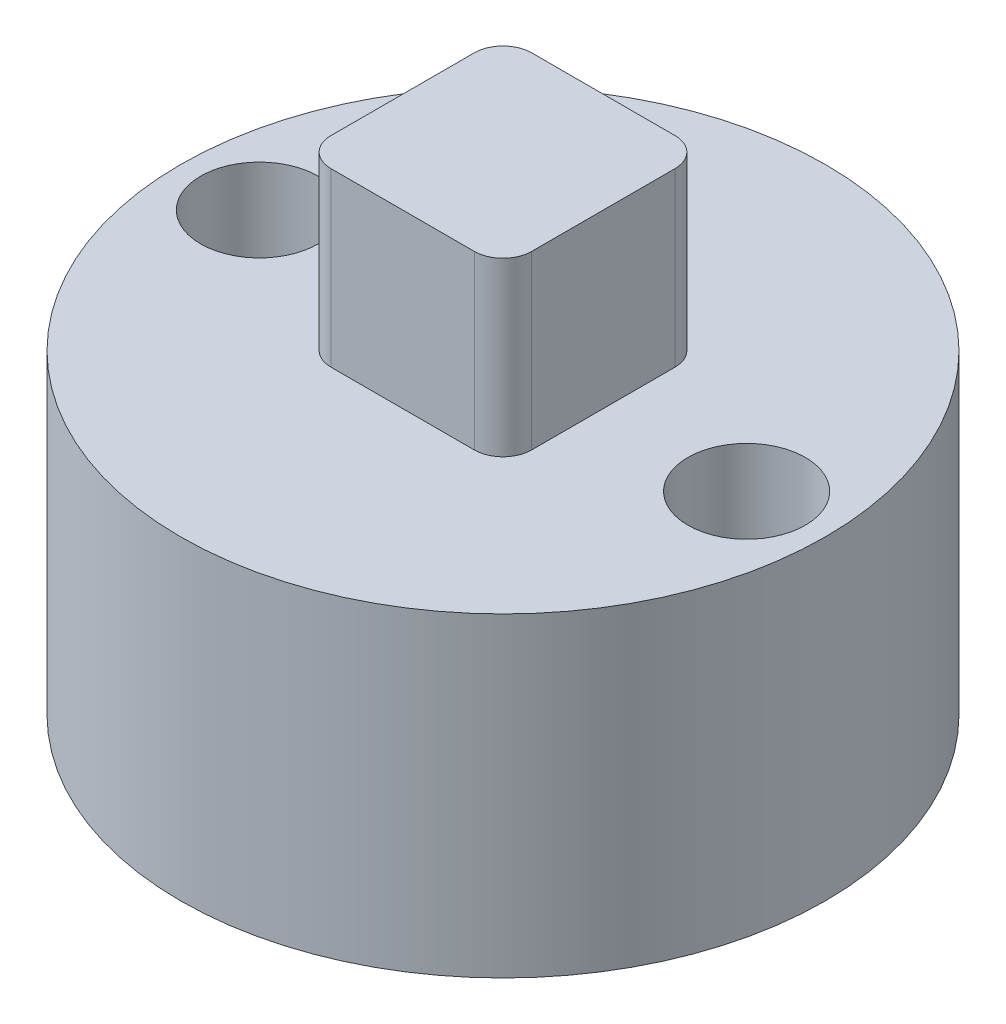
SolidWorks part; units mm, degrees
ref_plane "前视基准面" through (0, 0, 0) normal (0, 0, 1) x (1, 0, 0)
ref_plane "上视基准面" through (0, 0, 0) normal (0, 1, 0) x (1, 0, 0)
ref_plane "右视基准面" through (0, 0, 0) normal (1, 0, 0) x (0, 0, -1)
sketch "草图1" plane through (0, 0, 0) normal (0, 1, 0) x (1, 0, 0)
  circle A0 centre (0, 0) radius 11.25
  dimension "D1" = 22.5
extrude "凸台-拉伸1" add sketch "草图1" along normal blind 11
sketch "草图2" plane through (0, 0, 0) normal (0, -1, 0) x (1, 0, 0)
  line L0 (0, 0) -> (8.5, 0) construction
  line L1 (0, 0) -> (0, 4.3875) construction
  circle A0 centre (8.5, 0) radius 1.15
  circle A1 centre (-8.5, 0) radius 1.15
  dimension "D1" = 2.3
  dimension "D2" = 17
extrude "切除-拉伸1" cut sketch "草图2" against normal through all
sketch "草图3" plane through (0, 0, 0) normal (0, -1, 0) x (1, 0, 0)
  circle A0 centre (0, 0) radius 2.875
  dimension "D1" = 5.75
extrude "凸台-拉伸2" [suppressed] add sketch "草图3" along normal blind 2
sketch "草图4" plane through (0, 11, 0) normal (0, 1, 0) x (1, 0, 0)
  line L1 (-3.5, -3.5) -> (3.5, -3.5)
  line L2 (-3.5, -3.5) -> (-3.5, 3.5)
  line L3 (-3.5, 3.5) -> (3.5, 3.5)
  line L4 (3.5, -3.5) -> (3.5, 3.5)
  line L5 (-3.5, -3.5) -> (3.5, 3.5) construction
  line L6 (-3.5, 3.5) -> (3.5, -3.5) construction
  point P0 (0, 0)
  point P6 (1.9917, 7.4653)
  point P7 (3.2135, 3.6779)
  dimension "D1" = 7
  dimension "D2" = 7
extrude "凸台-拉伸3" add sketch "草图4" along normal blind 6
sketch "草图5" plane through (0, 11, 0) normal (0, 1, 0) x (1, 0, 0)
  circle A0 centre (8.5, 0) radius 2.05
  circle A1 centre (-8.5, 0) radius 2.05
  dimension "D1" = 4.1
extrude "切除-拉伸2" cut sketch "草图5" against normal offset from surface (9.5 mm away) 1.5 up to face at (8.5, 0, -1.15)
fillet "圆角1" radius 1 4 edges at (-3.5, 14, 3.5) (3.5, 14, 3.5) (3.5, 14, -3.5) (-3.5, 14, -3.5)
